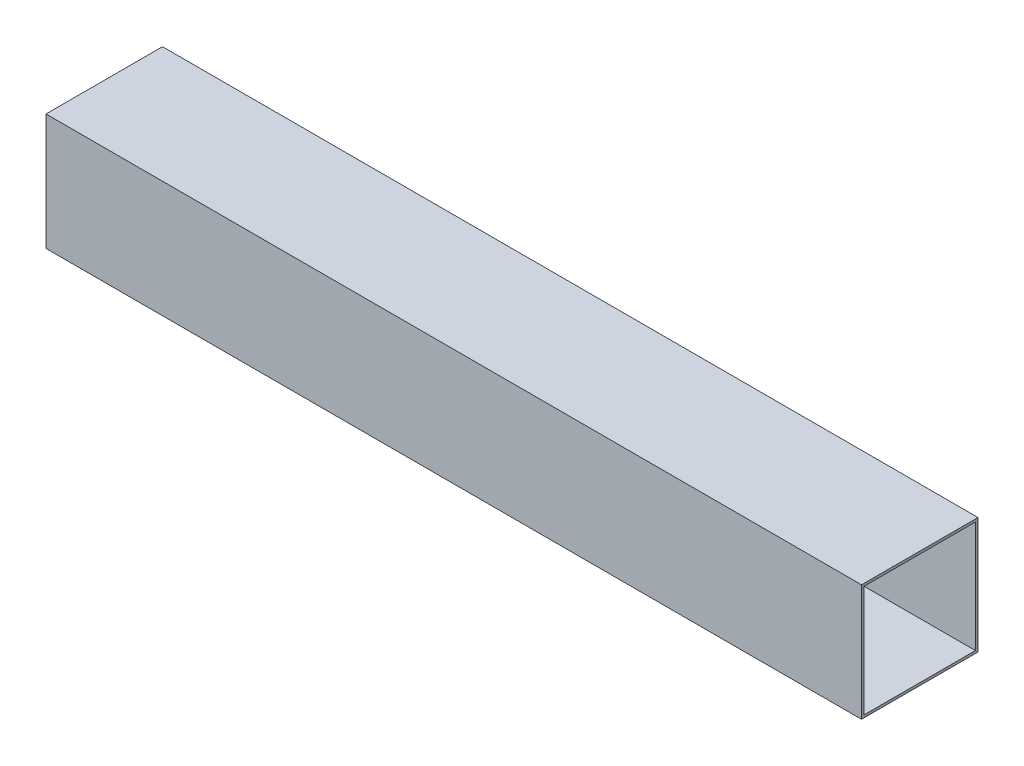
SolidWorks part; units mm, degrees
ref_plane "Alzado" through (0, 0, 0) normal (0, 0, 1) x (1, 0, 0)
ref_plane "Planta" through (0, 0, 0) normal (0, 1, 0) x (1, 0, 0)
ref_plane "Vista lateral" through (0, 0, 0) normal (1, 0, 0) x (0, 0, -1)
sketch "Croquis1" plane through (0, 0, 0) normal (0, 0, 1) x (1, 0, 0)
  line L0 (0, 0) -> (177.8, 0)
  dimension "D1" = 177.8
other "Al tube (square) 1 SQ X .022 WALL(5)"
ref_plane "Plano1" through (0, 0, 0) normal (1, 0, 0) x (0, 1, 0)
sketch "Sketch11" plane through (0, 0, 0) normal (1, 0, 0) x (0, 1, 0)
  line L0 (-12.1412, -12.1412) -> (-12.1412, 12.1412)
  line L1 (12.1412, 12.1412) -> (-12.1412, 12.1412)
  line L2 (12.1412, 12.1412) -> (12.1412, -12.1412)
  line L3 (-12.1412, -12.1412) -> (12.1412, -12.1412)
  line L4 (-12.7, -12.7) -> (12.7, -12.7)
  line L5 (-12.7, -12.7) -> (-12.7, 12.7)
  line L6 (12.7, 12.7) -> (-12.7, 12.7)
  line L7 (12.7, 12.7) -> (12.7, -12.7)
  line L8 (0, -12.1412) -> (0, -12.7) construction
  line L9 (0, -12.1412) -> (0, 12.1412) construction
  line L10 (0, 12.1412) -> (0, 12.7) construction
  line L11 (12.7, 0) -> (12.1412, 0) construction
  line L12 (12.1412, 0) -> (-12.1412, 0) construction
  line L13 (-12.1412, 0) -> (-12.7, 0) construction
  point P14 (0, 0)
  dimension "Thickness" = 0.5588
  dimension "V_leg" = 25.4
  dimension "H_leg" = 25.4
